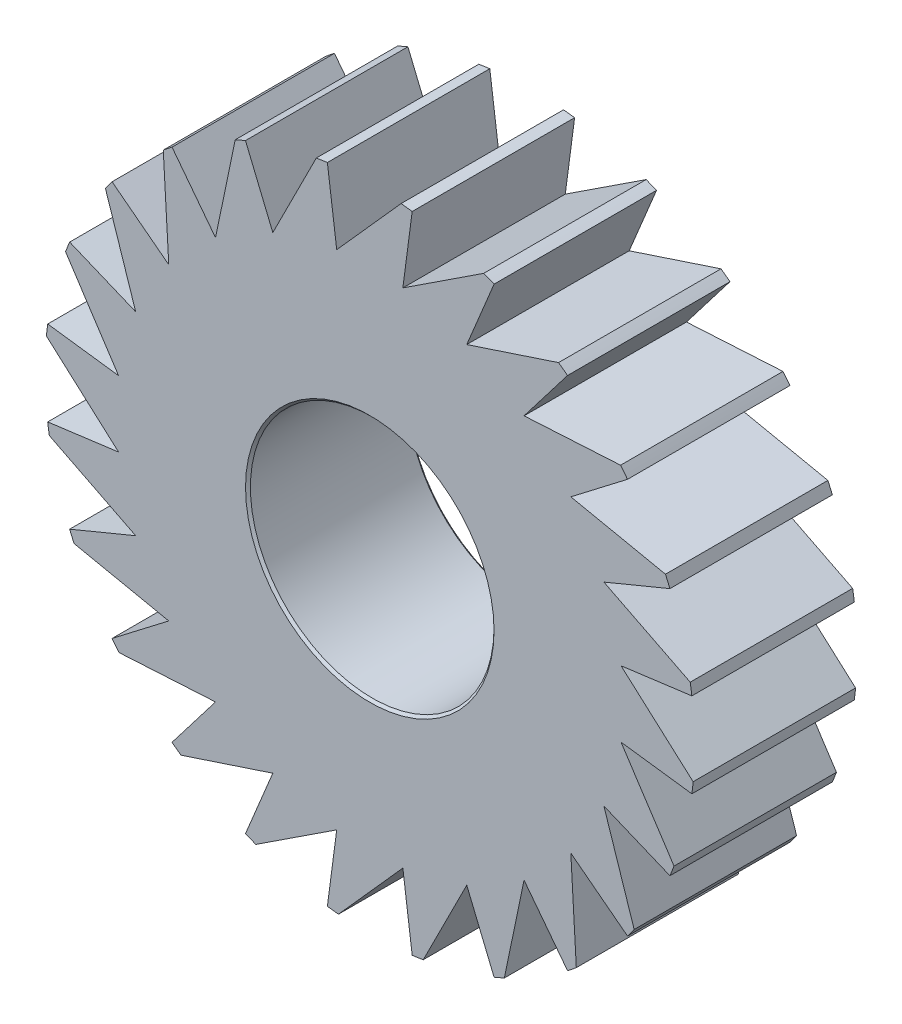
SolidWorks part; units mm, degrees
ref_plane "Front" through (0, 0, 0) normal (0, 0, 1) x (1, 0, 0)
ref_plane "Top" through (0, 0, 0) normal (0, 1, 0) x (1, 0, 0)
ref_plane "Right" through (0, 0, 0) normal (1, 0, 0) x (0, 0, -1)
sketch "Sketch1" plane through (0, 0, 0) normal (0, 0, 1) x (1, 0, 0)
  line L0 (-304.8, 0) -> (304.8, 0) construction
  circle A0 centre (0, 0) radius 12.7 construction
  circle A1 centre (0, 0) radius 13.335 construction
  circle A2 centre (0, 0) radius 4.7625
  circle A3 centre (0, 0) radius 9.906
  point P8 (0, 12.7)
  point P9 (0, -12.7)
  dimension "D1" = 19.812
  dimension "D2" = 26.67
extrude "Boss-Extrude1" add sketch "Sketch1" against normal blind 6.35
sketch "Sketch2" plane through (0, 0, 0) normal (0, 0, 1) x (1, 0, 0)
  line L0 (0, 0) -> (0, 12.7) construction
  line L1 (0, 0) -> (-1.293, 9.8213) construction
  line L2 (0, 0) -> (1.7406, 13.2209) construction
  line L3 (-1.293, 9.8213) -> (1.293, 9.8213) construction
  line L4 (-1.293, 9.8213) -> (1.7406, 13.2209)
  line L5 (1.7406, 13.2209) -> (1.293, 9.8213)
  circle A0 centre (0, 0) radius 12.7 construction
  circle A1 centre (0, 0) radius 13.335 construction
  circle A2 centre (0, 0) radius 9.906 construction
  arc A4 (1.293, 9.8213) -> (-1.293, 9.8213) centre (0, 0) ccw
  point P11 (0, 9.8213)
  dimension "D1" = 15
extrude "Boss-Extrude2" add sketch "Sketch2" against normal blind 6.35
pattern_circular "CirPattern1" count 24 over 360 about axis through (0, 0, 0) along (0, 0, 1) of "Boss-Extrude2"
chamfer "Chamfer1" distance 0.0953 angle 45 2 edges at (4.7625, 0, -6.35) (4.7625, 0, 0)
sketch "Pawl" plane through (0, 0, 0) normal (0, 0, 1) x (1, 0, 0)
  line L0 (1.6577, 12.5913) -> (4.4531, 11.8937) construction
  line L1 (1.293, 9.8213) -> (1.7406, 13.2209) construction
  line L2 (5.1031, 12.3199) -> (1.293, 9.8213) construction
  circle A0 centre (0, 0) radius 12.7 construction
  point P4 (3.0554, 12.2425)
  line B0 (3.0554, 13.0045) -> (3.0554, 12.2425)
  circle B1 centre (19.7242, 13.0363) radius 1.1906
  arc B2 (19.0678, 10.7473) -> (19.7242, 15.4175) centre (19.7242, 13.0363) ccw
  arc B3 (8.0376, 15.4175) -> (3.0554, 13.0045) centre (8.0376, 9.0675) ccw
  arc B4 (10.6187, 13.17) -> (3.8174, 12.2425) centre (7.9399, 7.4127) ccw
sketch_block_instance "Block1-1"
sketch_block "Block1"
sketch "Ref" plane through (0, 0, 0) normal (1, 0, 0) x (0, 0, -1)
  line L0 (0.0952, 4.7625) -> (6.2548, 4.7625) construction
  line L1 (6.2548, 4.7625) -> (6.35, 4.8578) construction
  line L2 (0.0952, 4.7625) -> (0, 4.8577) construction
  line L3 (0, -5.9543) -> (0.0952, -4.7625) construction
  line L4 (0, -8.1178) -> (0, -3.7909) construction
  line L5 (0.0952, -4.7625) -> (6.2548, -4.7625) construction
  line L6 (6.2548, -4.7625) -> (6.35, -4.8578) construction
sketch "Sketch3" plane through (0, 0, 0) normal (0, 0, 1) x (1, 0, 0)
  circle A0 centre (0, 0) radius 12.7 construction
  circle A1 centre (0, 0) radius 12.7
extrude "Cut-Extrude-Thin1" cut sketch "Sketch3" against normal through all flip side to cut thin
equation "\"D1@Sketch2\" = 360/\"Teeth@Sketch1\""
equation "\"D1@Boss-Extrude2\" = \"D1@Boss-Extrude1\""
equation "\"D1@CirPattern1\" = \"Teeth@Sketch1\""
equation "\"D1@Chamfer1\" = \"Bore Dia.@Sketch1\"*.01"
equation "\"D1@Sketch1\"=\"OD@Sketch1\"-.22"
equation "\"D2@Sketch1\"=\"OD@Sketch1\"+.05"
